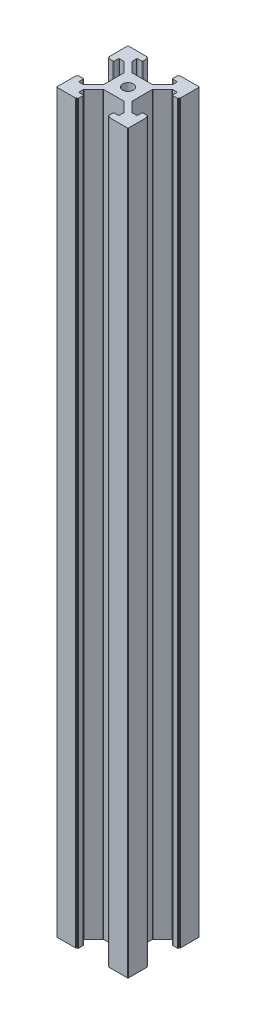
SolidWorks part; units mm, degrees
material "6063-O"
ref_plane "Ön Düzlem" through (0, 0, 0) normal (0, 0, 1) x (1, 0, 0)
ref_plane "Üst Düzlem" through (0, 0, 0) normal (0, 1, 0) x (1, 0, 0)
ref_plane "Sağ Düzlem" through (0, 0, 0) normal (1, 0, 0) x (0, 0, -1)
sketch "Sketch1" plane through (0, 0, 0) normal (0, 1, 0) x (1, 0, 0)
  line L0 (-10, 4.65) -> (-9.8, 4.65)
  line L1 (-9.8, -10) -> (-4.65, -10)
  line L2 (-10, -9.8) -> (-10, -4.65)
  line L3 (-9.8, 10) -> (-4.65, 10)
  line L4 (10, -9.8) -> (10, -4.65)
  line L5 (-10, -10) -> (10, 10) construction
  line L6 (-10, 10) -> (10, -10) construction
  line L7 (-9.8, 4.65) -> (-9.8, 4.4)
  line L8 (-9.6, 4.2) -> (-8.4, 4.2)
  line L9 (-4, 2.8172) -> (-4, -2.8172)
  line L10 (-8.2, 4.4) -> (-8.2, 5.45)
  line L11 (-8, 5.65) -> (-6.8328, 5.65)
  line L12 (-6.6914, 5.5914) -> (-4.0586, 2.9586)
  line L13 (-9.8, -4.65) -> (-10, -4.65)
  line L14 (-6.6914, -5.5914) -> (-4.0586, -2.9586)
  line L15 (-8, -5.65) -> (-6.8328, -5.65)
  line L16 (-8.2, -4.4) -> (-8.2, -5.45)
  line L17 (-9.6, -4.2) -> (-8.4, -4.2)
  line L18 (-9.8, -4.65) -> (-9.8, -4.4)
  line L19 (4.65, 10) -> (4.65, 9.8)
  line L20 (-10, 4.65) -> (-10, 9.8)
  line L21 (4.65, 9.8) -> (4.4, 9.8)
  line L22 (4.2, 9.6) -> (4.2, 8.4)
  line L23 (4.4, 8.2) -> (5.45, 8.2)
  line L24 (5.65, 8) -> (5.65, 6.8328)
  line L25 (5.5914, 6.6914) -> (2.9586, 4.0586)
  line L26 (2.8172, 4) -> (-2.8172, 4)
  line L27 (-5.5914, 6.6914) -> (-2.9586, 4.0586)
  line L28 (-5.65, 8) -> (-5.65, 6.8328)
  line L29 (-4.4, 8.2) -> (-5.45, 8.2)
  line L30 (-4.2, 9.6) -> (-4.2, 8.4)
  line L31 (-4.65, 9.8) -> (-4.4, 9.8)
  line L32 (-4.65, 9.8) -> (-4.65, 10)
  line L33 (10, -4.65) -> (9.8, -4.65)
  line L34 (9.8, -4.65) -> (9.8, -4.4)
  line L35 (9.6, -4.2) -> (8.4, -4.2)
  line L36 (8.2, -4.4) -> (8.2, -5.45)
  line L37 (8, -5.65) -> (6.8328, -5.65)
  line L38 (6.6914, -5.5914) -> (4.0586, -2.9586)
  line L39 (4, -2.8172) -> (4, 2.8172)
  line L40 (6.6914, 5.5914) -> (4.0586, 2.9586)
  line L41 (8, 5.65) -> (6.8328, 5.65)
  line L42 (8.2, 4.4) -> (8.2, 5.45)
  line L43 (9.6, 4.2) -> (8.4, 4.2)
  line L44 (9.8, 4.65) -> (9.8, 4.4)
  line L45 (9.8, 4.65) -> (10, 4.65)
  line L46 (-4.65, -10) -> (-4.65, -9.8)
  line L47 (-4.65, -9.8) -> (-4.4, -9.8)
  line L48 (-4.2, -9.6) -> (-4.2, -8.4)
  line L49 (-4.4, -8.2) -> (-5.45, -8.2)
  line L50 (-5.65, -8) -> (-5.65, -6.8328)
  line L51 (-5.5914, -6.6914) -> (-2.9586, -4.0586)
  line L52 (-2.8172, -4) -> (2.8172, -4)
  line L53 (5.5914, -6.6914) -> (2.9586, -4.0586)
  line L54 (5.65, -8) -> (5.65, -6.8328)
  line L55 (4.4, -8.2) -> (5.45, -8.2)
  line L56 (4.2, -9.6) -> (4.2, -8.4)
  line L57 (4.65, -9.8) -> (4.4, -9.8)
  line L58 (4.65, -9.8) -> (4.65, -10)
  line L59 (4.65, -10) -> (9.8, -10)
  line L60 (10, 4.65) -> (10, 9.8)
  line L61 (4.65, 10) -> (9.8, 10)
  arc A0 (-9.8, 4.4) -> (-9.6, 4.2) centre (-9.6, 4.4) ccw
  arc A1 (-9.8, -4.4) -> (-9.6, -4.2) centre (-9.6, -4.4) cw
  arc A2 (-8.4, 4.2) -> (-8.2, 4.4) centre (-8.4, 4.4) ccw
  arc A3 (-8.2, 5.45) -> (-8, 5.65) centre (-8, 5.45) cw
  arc A4 (-6.6914, 5.5914) -> (-6.8328, 5.65) centre (-6.8328, 5.45) ccw
  arc A5 (-4, 2.8172) -> (-4.0586, 2.9586) centre (-4.2, 2.8172) ccw
  arc A6 (-6.6914, -5.5914) -> (-6.8328, -5.65) centre (-6.8328, -5.45) cw
  arc A7 (-4, -2.8172) -> (-4.0586, -2.9586) centre (-4.2, -2.8172) cw
  arc A8 (-8, -5.65) -> (-8.2, -5.45) centre (-8, -5.45) cw
  arc A9 (-8.2, -4.4) -> (-8.4, -4.2) centre (-8.4, -4.4) ccw
  arc A10 (4.4, 9.8) -> (4.2, 9.6) centre (4.4, 9.6) ccw
  arc A11 (4.2, 8.4) -> (4.4, 8.2) centre (4.4, 8.4) ccw
  arc A12 (5.45, 8.2) -> (5.65, 8) centre (5.45, 8) cw
  arc A13 (5.5914, 6.6914) -> (5.65, 6.8328) centre (5.45, 6.8328) ccw
  arc A14 (2.8172, 4) -> (2.9586, 4.0586) centre (2.8172, 4.2) ccw
  arc A15 (-2.8172, 4) -> (-2.9586, 4.0586) centre (-2.8172, 4.2) cw
  arc A16 (-5.5914, 6.6914) -> (-5.65, 6.8328) centre (-5.45, 6.8328) cw
  arc A17 (-5.65, 8) -> (-5.45, 8.2) centre (-5.45, 8) cw
  arc A18 (-4.4, 8.2) -> (-4.2, 8.4) centre (-4.4, 8.4) ccw
  arc A19 (-4.4, 9.8) -> (-4.2, 9.6) centre (-4.4, 9.6) cw
  arc A20 (9.8, -4.4) -> (9.6, -4.2) centre (9.6, -4.4) ccw
  arc A21 (8.4, -4.2) -> (8.2, -4.4) centre (8.4, -4.4) ccw
  arc A22 (8.2, -5.45) -> (8, -5.65) centre (8, -5.45) cw
  arc A23 (6.6914, -5.5914) -> (6.8328, -5.65) centre (6.8328, -5.45) ccw
  arc A24 (4, -2.8172) -> (4.0586, -2.9586) centre (4.2, -2.8172) ccw
  arc A25 (4, 2.8172) -> (4.0586, 2.9586) centre (4.2, 2.8172) cw
  arc A26 (6.6914, 5.5914) -> (6.8328, 5.65) centre (6.8328, 5.45) cw
  arc A27 (8, 5.65) -> (8.2, 5.45) centre (8, 5.45) cw
  arc A28 (8.2, 4.4) -> (8.4, 4.2) centre (8.4, 4.4) ccw
  arc A29 (9.8, 4.4) -> (9.6, 4.2) centre (9.6, 4.4) cw
  arc A30 (-4.4, -9.8) -> (-4.2, -9.6) centre (-4.4, -9.6) ccw
  arc A31 (-4.2, -8.4) -> (-4.4, -8.2) centre (-4.4, -8.4) ccw
  arc A32 (-5.45, -8.2) -> (-5.65, -8) centre (-5.45, -8) cw
  arc A33 (-5.5914, -6.6914) -> (-5.65, -6.8328) centre (-5.45, -6.8328) ccw
  arc A34 (-2.8172, -4) -> (-2.9586, -4.0586) centre (-2.8172, -4.2) ccw
  arc A35 (2.8172, -4) -> (2.9586, -4.0586) centre (2.8172, -4.2) cw
  arc A36 (5.5914, -6.6914) -> (5.65, -6.8328) centre (5.45, -6.8328) cw
  arc A37 (5.65, -8) -> (5.45, -8.2) centre (5.45, -8) cw
  arc A38 (4.4, -8.2) -> (4.2, -8.4) centre (4.4, -8.4) ccw
  arc A39 (4.4, -9.8) -> (4.2, -9.6) centre (4.4, -9.6) cw
  arc A40 (-9.8, -10) -> (-10, -9.8) centre (-9.8, -9.8) cw
  arc A41 (9.8, -10) -> (10, -9.8) centre (9.8, -9.8) ccw
  arc A42 (10, 9.8) -> (9.8, 10) centre (9.8, 9.8) ccw
  arc A43 (-10, 9.8) -> (-9.8, 10) centre (-9.8, 9.8) cw
  circle A44 centre (0, 0) radius 1.5
  point P0 (0, 0)
  point P12 (-9.8, 4.2)
  point P27 (-9.8, -4.2)
  point P30 (-8.2, 4.2)
  point P33 (-8.2, 5.65)
  point P36 (-6.75, 5.65)
  point P39 (-4, 2.9)
  point P42 (-6.75, -5.65)
  point P45 (-4, -2.9)
  point P48 (-8.2, -5.65)
  point P51 (-8.2, -4.2)
  dimension "D11" = 0.2
  dimension "D13" = 0.2
  dimension "D14" = 3
  dimension "D1" = 20
  dimension "D2" = 20
  dimension "D3" = 5.35
  dimension "D4" = 0.2
  dimension "D5" = 0.45
  dimension "D6" = 1.6
  dimension "D7" = 4.2
  dimension "D8" = 1.45
  dimension "D9" = 1.45
  dimension "D10" = 135
  dimension "D12" = 4
extrude "Boss-Extrude1" add sketch "Sketch1" along normal blind 206
sketch "Sketch2" plane through (4, 0, 0) normal (1, 0, 0) x (0, 0, -1)
  line L0 (0, 206) -> (0, 0)
  line L1 (-2.8172, 206) -> (2.8172, 206) construction
  circle A0 centre (0, 103) radius 1.5
  line M2 (2.8172, 0) -> (2.8172, 206)
  line M4 (-2.8172, 206) -> (-2.8172, 0)
  dimension "D1" = 3
extrude "Cut-Extrude1" cut sketch "Sketch2" against normal blind 10 and the other way blind 10 contours A0 L0 M2 | L0 A0 M4
sketch "Sketch3" plane through (0, 0, 10) normal (0, 0, 1) x (1, 0, 0)
  line L0 (0, 206) -> (0, 0)
  line L1 (-2.8172, 206) -> (2.8172, 206) construction
sketch "Sketch4" plane through (0, 0, 4) normal (0, 0, 1) x (1, 0, 0)
  circle A0 centre (0, 103) radius 1.5
  dimension "D1" = 3
  dimension "D2" = 103
extrude "Cut-Extrude2" cut sketch "Sketch4" against normal blind 10 and the other way blind 10
